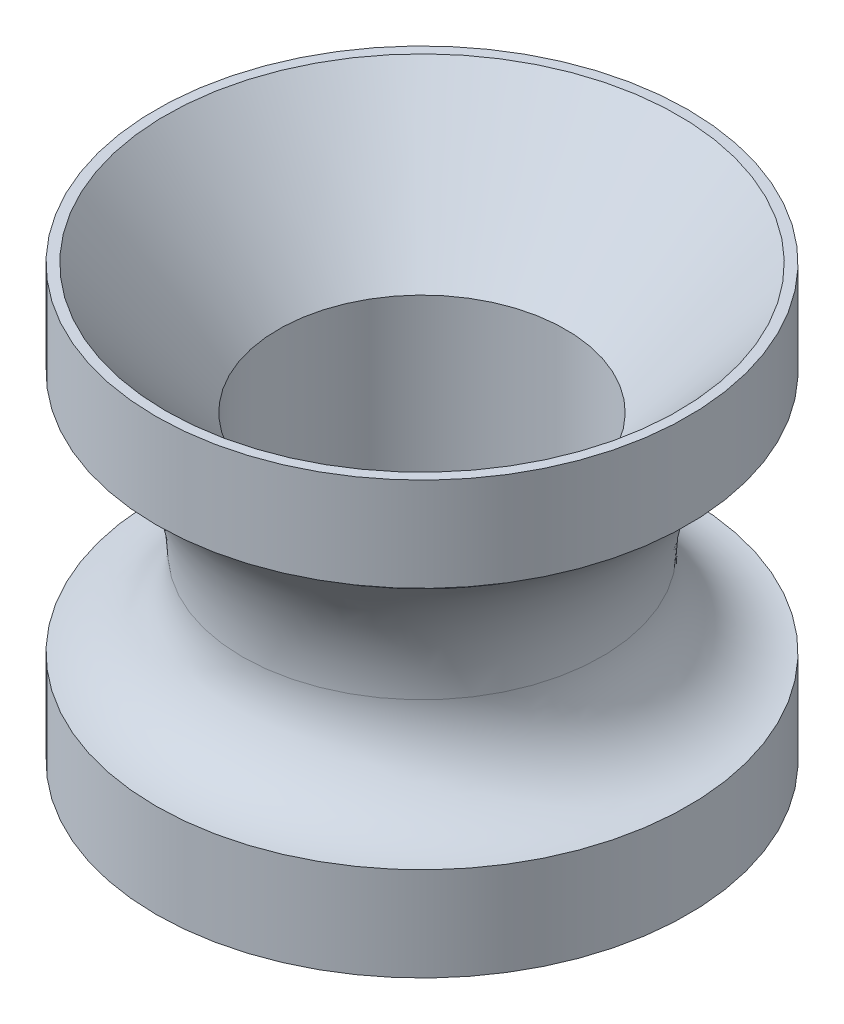
SolidWorks part; units mm, degrees
material "Plain Carbon Steel"
ref_plane "Front Plane" through (0, 0, 0) normal (0, 0, 1) x (1, 0, 0)
ref_plane "Top Plane" through (0, 0, 0) normal (0, 1, 0) x (1, 0, 0)
ref_plane "Right Plane" through (0, 0, 0) normal (1, 0, 0) x (0, 0, -1)
sketch "Sketch1" plane through (0, 0, 0) normal (0, 0, 1) x (1, 0, 0)
  line L0 (0, 0) -> (4.699, 0)
  line L1 (4.699, 0) -> (4.699, 1.6568)
  line L5 (4.699, 5.9632) -> (4.699, 7.62)
  line L6 (4.699, 7.62) -> (0, 7.62)
  line L7 (0, 7.62) -> (0, 0)
  line L8 (4.699, 1.6568) -> (5.175, 1.6568) construction
  arc A0 (4.699, 1.6568) -> (3.175, 3.1808) centre (4.699, 3.1808) cw
  arc A1 (3.175, 3.1808) -> (4.699, 5.9632) centre (6.477, 3.1808) cw
  point P10 (4.699, 6.2024)
  point P11 (3.175, 3.1808)
  point P12 (4.699, 1.6568)
  point P13 (4.699, 3.1808)
  point P14 (5.175, 1.6568)
  dimension "D2" = 3.302
  dimension "D5" = 1.524
  dimension "D1" = 7.62
  dimension "D3" = 4.699
  dimension "D4" = 3.175
revolve "Revolve1" add sketch "Sketch1" angle 360 about L7
sketch "Sketch2" plane through (0, 0, 0) normal (0, 0, 1) x (1, 0, 0)
  line L0 (0, 0) -> (2.54, 0)
  line L1 (-4.699, 0) -> (4.699, 0) construction
  line L2 (2.54, 0) -> (2.54, 5.334)
  line L3 (2.54, 5.334) -> (4.5272, 7.62)
  line L4 (4.699, 7.62) -> (-4.699, 7.62) construction
  line L5 (4.5272, 7.62) -> (0, 7.62)
  line L6 (0, 7.62) -> (0, 0)
  dimension "D1" = 5.334
  dimension "D2" = 139
  dimension "D3" = 2.54
revolve "Cut-Revolve1" cut sketch "Sketch2" angle 360 about L6
